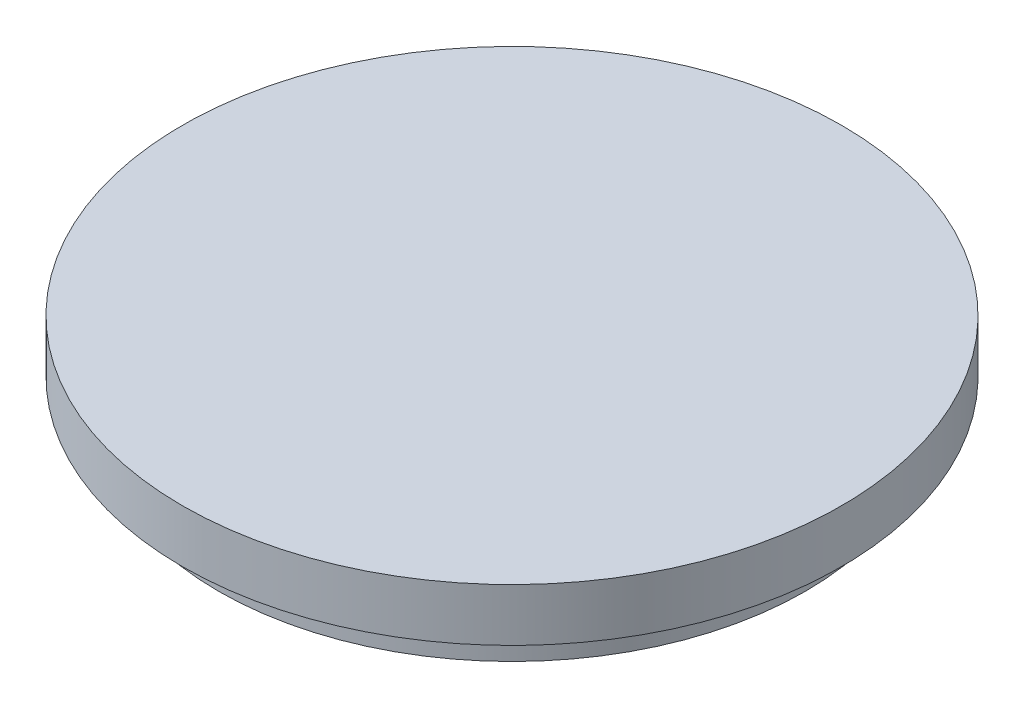
SolidWorks part; units mm, degrees
ref_plane "Front Plane" through (0, 0, 0) normal (0, 0, 1) x (1, 0, 0)
ref_plane "Top Plane" through (0, 0, 0) normal (0, 1, 0) x (1, 0, 0)
ref_plane "Right Plane" through (0, 0, 0) normal (1, 0, 0) x (0, 0, -1)
sketch "Sketch1" plane through (0, 0, 0) normal (0, 0, 1) x (1, 0, 0)
  line L0 (0, 16.9027) -> (0, -14.5012) construction
  line L1 (-12.5, 4.4938) -> (-12.5, 2.4938)
  line L2 (-12.5, 2.4938) -> (-11.125, 2.4938)
  line L3 (-11.125, 2.4938) -> (-11.125, 0.9938)
  line L4 (-11.125, 0.9938) -> (0, 0.9938)
  line L5 (0, 0.9938) -> (0, 4.4938)
  line L6 (0, 4.4938) -> (-12.5, 4.4938)
  dimension "D1" = 25
  dimension "D2" = 22.25
  dimension "D3" = 1.5
  dimension "D4" = 2
revolve "Revolve1" add sketch "Sketch1" angle 360 about L0
